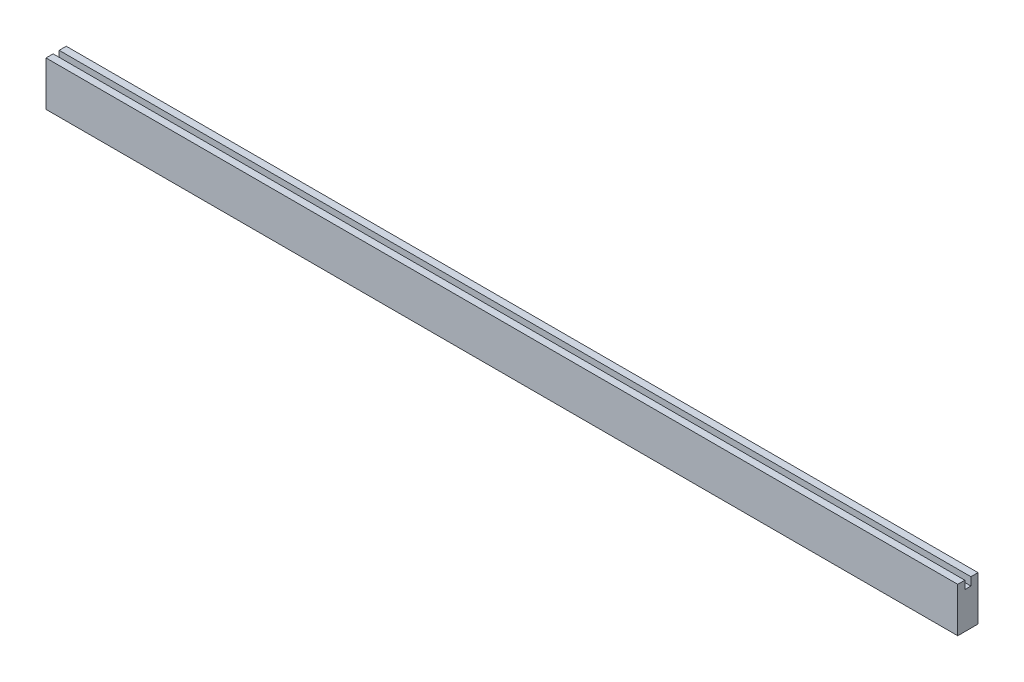
SolidWorks part; units mm, degrees
material "Buk"
ref_plane "Płaszczyzna przednia" through (0, 0, 0) normal (0, 0, 1) x (1, 0, 0)
ref_plane "Płaszczyzna górna" through (0, 0, 0) normal (0, 1, 0) x (1, 0, 0)
ref_plane "Płaszczyzna prawa" through (0, 0, 0) normal (1, 0, 0) x (0, 0, -1)
sketch "Szkic1" plane through (0, 0, 0) normal (0, 1, 0) x (1, 0, 0)
  line L1 (-247.6236, 0) -> (202.3764, 0)
  line L2 (-247.6236, 0) -> (-247.6236, 10)
  line L3 (-247.6236, 10) -> (202.3764, 10)
  line L4 (202.3764, 0) -> (202.3764, 10)
  dimension "D1" = 450
  dimension "D2" = 10
extrude "Dodanie-wyciągnięcie1" add sketch "Szkic1" along normal blind 22
sketch "Szkic2" plane through (0, 22, 0) normal (0, 1, 0) x (1, 0, 0)
  line L0 (-247.6236, 10) -> (-247.6236, 0) construction
  line L1 (-247.6236, 6.5) -> (202.3764, 6.5)
  line L2 (-247.6236, 6.5) -> (-247.6236, 3.5)
  line L3 (-247.6236, 3.5) -> (202.3764, 3.5)
  line L4 (202.3764, 6.5) -> (202.3764, 3.5)
  line L5 (202.3764, 0) -> (202.3764, 10) construction
  line L6 (202.3764, 10) -> (-247.6236, 10) construction
  dimension "D1" = 3
  dimension "D2" = 3.5
extrude "Wytnij-wyciągnięcie1" cut sketch "Szkic2" against normal blind 4
hole_wizard "Otwory ustalające Ø3.0mm1" positions "Szkic3" profile "Szkic4" hole size "Ø3.0" standard "Ansi Metric"
sketch "Szkic3" plane through (0, 0, 0) normal (0, -1, 0) x (-1, 0, 0)
  point P0 (-77.3764, 5)
  point P3 (122.6236, 5)
sketch "Szkic4" plane through (77.3764, 0, -5) normal (1, 0, 0) x (0, 0, -1)
  line L0 (0, 0) -> (0, 10.9013)
  line L1 (0, 10.9013) -> (1.5, 10)
  line L2 (1.5, 10) -> (1.5, 0)
  line L5 (1.5, 0) -> (0, 0)
  line L10 (0, 10.9013) -> (-1.5, 10) construction
  line L11 (0, -6.35) -> (0, 107.95) construction
  dimension "Œrednica otworu" = 3
  dimension "G³êbokoœæ otworu" = 10
  dimension "K¹t wiert³a" = 118
